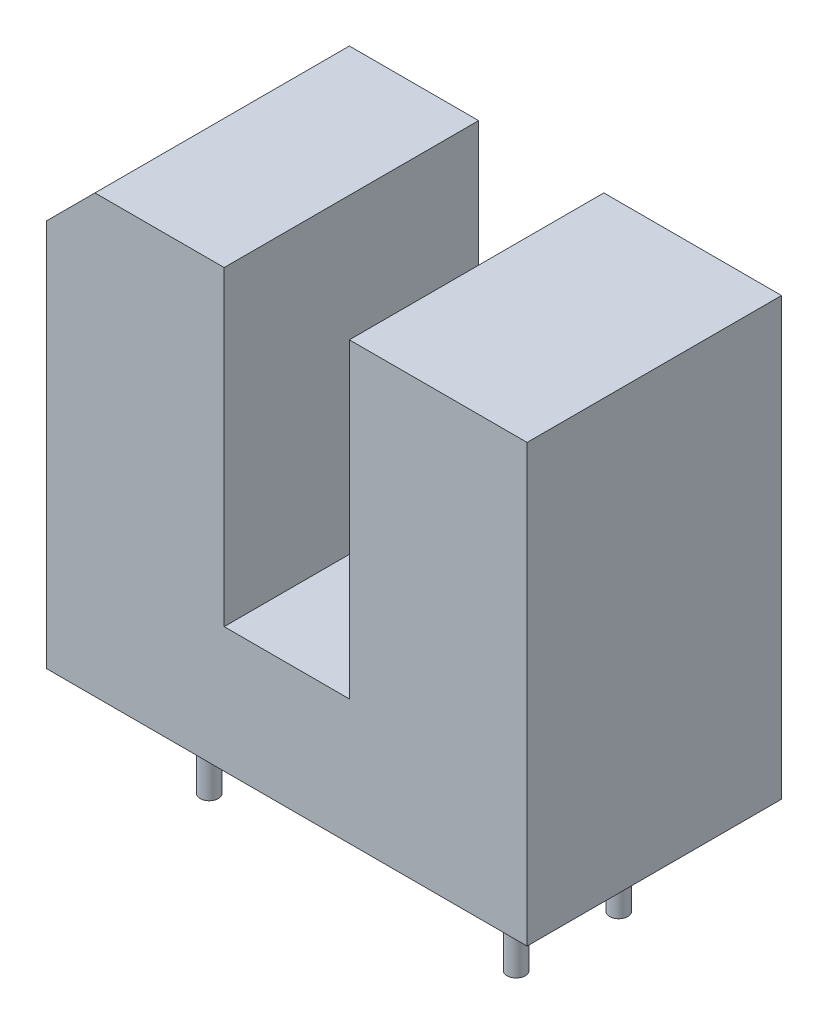
SolidWorks part; units mm, degrees
ref_plane "Спереди" through (0, 0, 0) normal (0, 0, 1) x (1, 0, 0)
ref_plane "Сверху" through (0, 0, 0) normal (0, 1, 0) x (1, 0, 0)
ref_plane "Справа" through (0, 0, 0) normal (1, 0, 0) x (0, 0, -1)
sketch "Sketch1" plane through (0, 0, 0) normal (0, 1, 0) x (1, 0, 0)
  line L1 (-5.95, 3.15) -> (5.95, 3.15)
  line L2 (-5.95, 3.15) -> (-5.95, -3.15)
  line L3 (-5.95, -3.15) -> (5.95, -3.15)
  line L4 (5.95, 3.15) -> (5.95, -3.15)
  line L5 (-5.95, 3.15) -> (5.95, -3.15) construction
  line L6 (-5.95, -3.15) -> (5.95, 3.15) construction
  point P0 (0, 0)
  dimension "D1" = 6.3
  dimension "D2" = 11.9
extrude "Boss-Extrude1" add sketch "Sketch1" along normal blind 3.1
sketch "Sketch2" plane through (0, 3.1, 0) normal (0, 1, 0) x (1, 0, 0)
  line L0 (-5.95, -3.15) -> (5.95, -3.15) construction
  line L1 (-5.95, 3.15) -> (-1.55, 3.15)
  line L2 (-5.95, 3.15) -> (-5.95, -3.15)
  line L3 (-5.95, -3.15) -> (-1.55, -3.15)
  line L4 (-1.55, 3.15) -> (-1.55, -3.15)
  line L6 (5.95, 3.15) -> (1.55, 3.15)
  line L7 (5.95, 3.15) -> (5.95, -3.15)
  line L8 (5.95, -3.15) -> (1.55, -3.15)
  line L9 (1.55, 3.15) -> (1.55, -3.15)
  dimension "D1" = 3.1
extrude "Boss-Extrude2" add sketch "Sketch2" along normal blind 7.7
sketch "Sketch3" plane through (1.55, 0, 0) normal (-1, 0, 0) x (0, 0, 1)
  line L0 (0, 10.8) -> (0, 8.2) construction
  line L1 (-3.15, 10.8) -> (3.15, 10.8) construction
  circle A0 centre (0, 8.2) radius 0.5
  dimension "D2" = 1
  dimension "D1" = 2.6
extrude "Cut-Extrude1" cut sketch "Sketch3" against normal blind 1
chamfer "Chamfer1" distance 1.2 angle 45 1 edges at (-5.95, 10.8, 0)
sketch "Sketch4" plane through (0, 0, 0) normal (0, -1, 0) x (1, 0, 0)
  line L1 (-3.8, 1.27) -> (3.8, 1.27) construction
  line L2 (-3.8, 1.27) -> (-3.8, -1.27) construction
  line L3 (-3.8, -1.27) -> (3.8, -1.27) construction
  line L4 (3.8, 1.27) -> (3.8, -1.27) construction
  line L5 (-3.8, 1.27) -> (3.8, -1.27) construction
  line L6 (-3.8, -1.27) -> (3.8, 1.27) construction
  circle A0 centre (-3.8, 1.27) radius 0.225
  circle A1 centre (-3.8, -1.27) radius 0.225
  circle A2 centre (3.8, 1.27) radius 0.225
  circle A3 centre (3.8, -1.27) radius 0.225
  point P0 (0, 0)
  dimension "D3" = 0.45
  dimension "D1" = 7.6
  dimension "D2" = 2.54
extrude "Boss-Extrude3" add sketch "Sketch4" along normal blind 2.54
